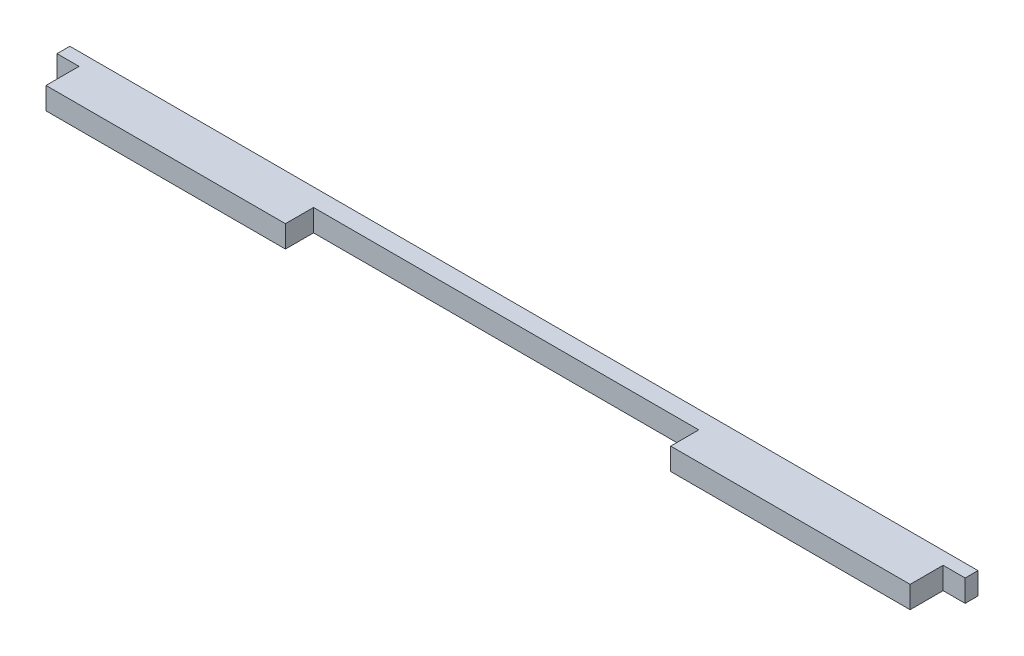
SolidWorks part; units mm, degrees
ref_plane "Front Plane" through (0, 0, 0) normal (0, 0, 1) x (1, 0, 0)
ref_plane "Top Plane" through (0, 0, 0) normal (0, 1, 0) x (1, 0, 0)
ref_plane "Right Plane" through (0, 0, 0) normal (1, 0, 0) x (0, 0, -1)
sketch "Sketch2" plane through (0, 0, 0) normal (0, 1, 0) x (1, 0, 0)
  line L1 (0, 0) -> (495, 0)
  line L2 (0, 0) -> (0, 25)
  line L3 (0, 25) -> (495, 25)
  line L4 (495, 0) -> (495, 25)
  line L5 (142.5, 0) -> (352.5, 0)
  line L6 (142.5, 0) -> (142.5, 15.3096)
  line L7 (142.5, 15.3096) -> (352.5, 15.3096)
  line L8 (352.5, 0) -> (352.5, 15.3096)
  point P9 (495, 12.5)
  dimension "D1" = 25
  dimension "D2" = 495
  dimension "D3" = 142.5
  dimension "D4" = 142.5
extrude "Boss-Extrude1" add sketch "Sketch2" along normal blind 12 contours L8 L1 L4 L3 L2 L6 L7
sketch "Sketch3" plane through (0, 12, 0) normal (0, 1, 0) x (1, 0, 0)
  line L0 (247.5, 25) -> (247.5, 0) construction
  line L1 (0, 0) -> (12, 0)
  line L2 (0, 0) -> (0, 18)
  line L3 (0, 18) -> (12, 18)
  line L4 (12, 0) -> (12, 18)
  line L5 (0, 25) -> (495, 25) construction
  line L6 (495, 18) -> (483, 18)
  line L7 (483, 0) -> (483, 18)
  line L8 (495, 0) -> (483, 0)
  line L9 (495, 0) -> (495, 18)
  dimension "D1" = 18
  dimension "D2" = 12
extrude "Cut-Extrude1" cut sketch "Sketch3" against normal blind 12
